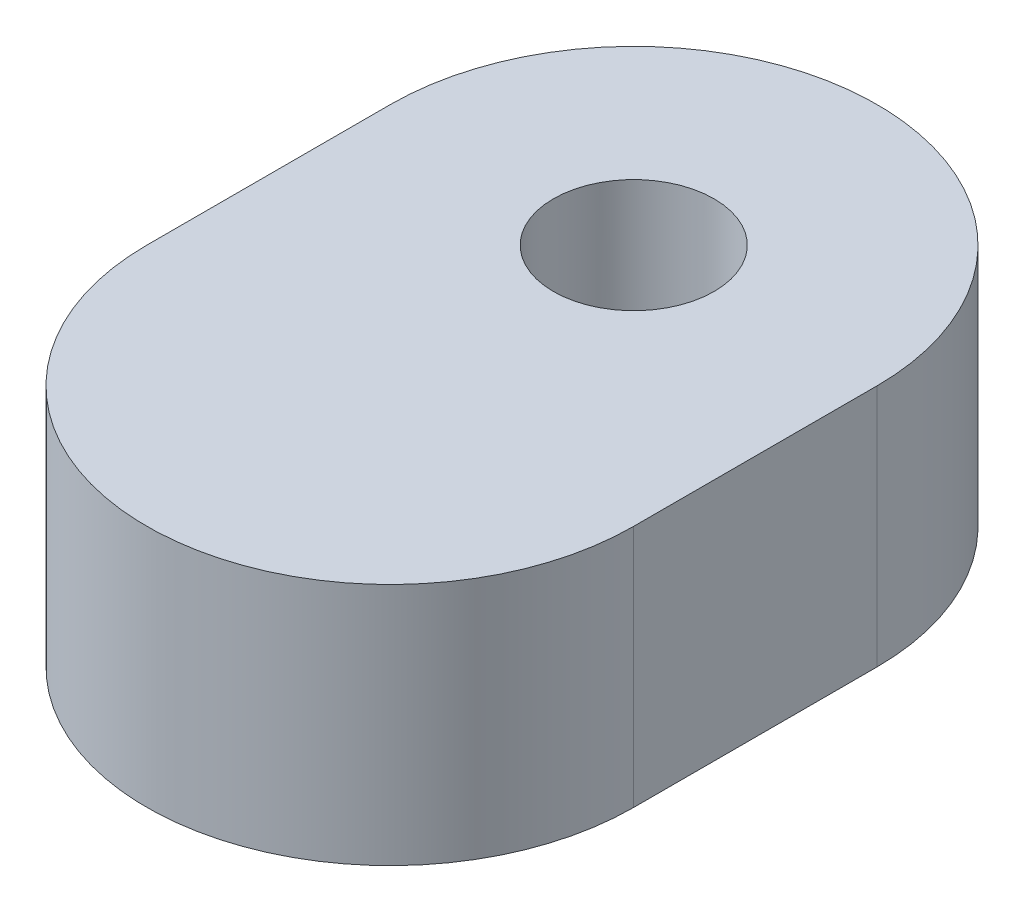
SolidWorks part; units mm, degrees
ref_plane "Front Plane" through (0, 0, 0) normal (0, 0, 1) x (1, 0, 0)
ref_plane "Top Plane" through (0, 0, 0) normal (0, 1, 0) x (1, 0, 0)
ref_plane "Right Plane" through (0, 0, 0) normal (1, 0, 0) x (0, 0, -1)
sketch "Sketch1" plane through (0, 0, 0) normal (0, 1, 0) x (1, 0, 0)
  line L0 (0, 0) -> (0, -10) construction
  line L1 (10, 0) -> (10, -10)
  line L2 (-10, 0) -> (-10, -10)
  circle A0 centre (0, 0) radius 3.3
  arc A1 (10, 0) -> (-10, 0) centre (0, 0) ccw
  arc A2 (-10, -10) -> (10, -10) centre (0, -10) ccw
  point P3 (0, -5)
  point P9 (0, -20)
  dimension "D1" = 20
  dimension "D2" = 6.6
  dimension "D3" = 20
extrude "Boss-Extrude1" add sketch "Sketch1" along normal blind 10
sketch "Sketch2" plane through (0, 0, 0) normal (0, -1, 0) x (1, 0, 0)
  line L1 (6.5, 3.7528) -> (0, 7.5056)
  line L2 (0, 7.5056) -> (-6.5, 3.7528)
  line L3 (-6.5, 3.7528) -> (-6.5, -3.7528)
  line L4 (-6.5, -3.7528) -> (0, -7.5056)
  line L5 (0, -7.5056) -> (6.5, -3.7528)
  line L6 (6.5, -3.7528) -> (6.5, 3.7528)
  circle A0 centre (0, 0) radius 6.5 construction
  dimension "D1" = 13
extrude "Cut-Extrude1" cut sketch "Sketch2" against normal blind 5
